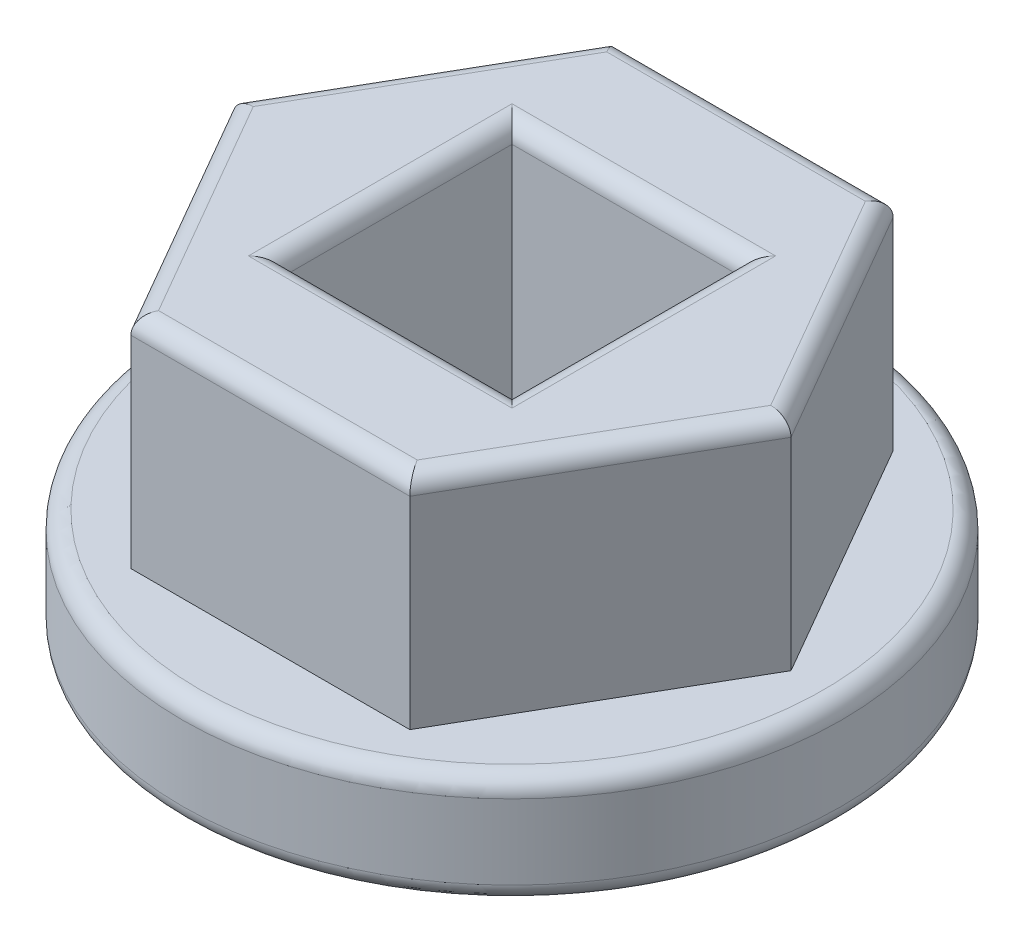
SolidWorks part; units mm, degrees
ref_plane "Front Plane" through (0, 0, 0) normal (0, 0, 1) x (1, 0, 0)
ref_plane "Top Plane" through (0, 0, 0) normal (0, 1, 0) x (1, 0, 0)
ref_plane "Right Plane" through (0, 0, 0) normal (1, 0, 0) x (0, 0, -1)
sketch "Sketch1" plane through (0, 0, 0) normal (0, 1, 0) x (1, 0, 0)
  line L1 (8.0656, 0) -> (4.0328, 6.985)
  line L2 (4.0328, 6.985) -> (-4.0328, 6.985)
  line L3 (-4.0328, 6.985) -> (-8.0656, 0)
  line L4 (-8.0656, 0) -> (-4.0328, -6.985)
  line L5 (-4.0328, -6.985) -> (4.0328, -6.985)
  line L6 (4.0328, -6.985) -> (8.0656, 0)
  line L7 (-3.302, 3.302) -> (3.302, 3.302)
  line L8 (-3.302, 3.302) -> (-3.302, -3.302)
  line L9 (-3.302, -3.302) -> (3.302, -3.302)
  line L10 (3.302, 3.302) -> (3.302, -3.302)
  line L11 (-3.302, 3.302) -> (3.302, -3.302) construction
  line L12 (-3.302, -3.302) -> (3.302, 3.302) construction
  circle A0 centre (0, 0) radius 6.985 construction
  dimension "D1" = 13.97
  dimension "D2" = 6.604
extrude "Boss-Extrude1" add sketch "Sketch1" along normal blind 6.35
sketch "Sketch2" plane through (0, 0, 0) normal (0, -1, 0) x (1, 0, 0)
  line L1 (-3.302, 3.302) -> (3.302, 3.302)
  line L2 (-3.302, 3.302) -> (-3.302, -3.302)
  line L3 (-3.302, -3.302) -> (3.302, -3.302)
  line L4 (3.302, 3.302) -> (3.302, -3.302)
  line L5 (-3.302, 3.302) -> (3.302, -3.302) construction
  line L6 (-3.302, -3.302) -> (3.302, 3.302) construction
  circle A0 centre (0, 0) radius 9.525
  dimension "D1" = 19.05
extrude "Boss-Extrude2" add sketch "Sketch2" along normal blind 3.175
fillet "Fillet1" radius 0.508 16 edges at (-3.302, 6.35, 0) (0, 6.35, 3.302) (3.302, 6.35, 0) (0, 6.35, -3.302) (0, 6.35, 6.985) (-6.0492, 6.35, 3.4925) (-6.0492, 6.35, -3.4925) (0, 6.35, -6.985) (6.0492, 6.35, -3.4925) (6.0492, 6.35, 3.4925) (-3.302, -3.175, 0) (0, -3.175, -3.302) (3.302, -3.175, 0) (0, -3.175, 3.302) (0, -3.175, -9.525) (0, 0, -9.525)
